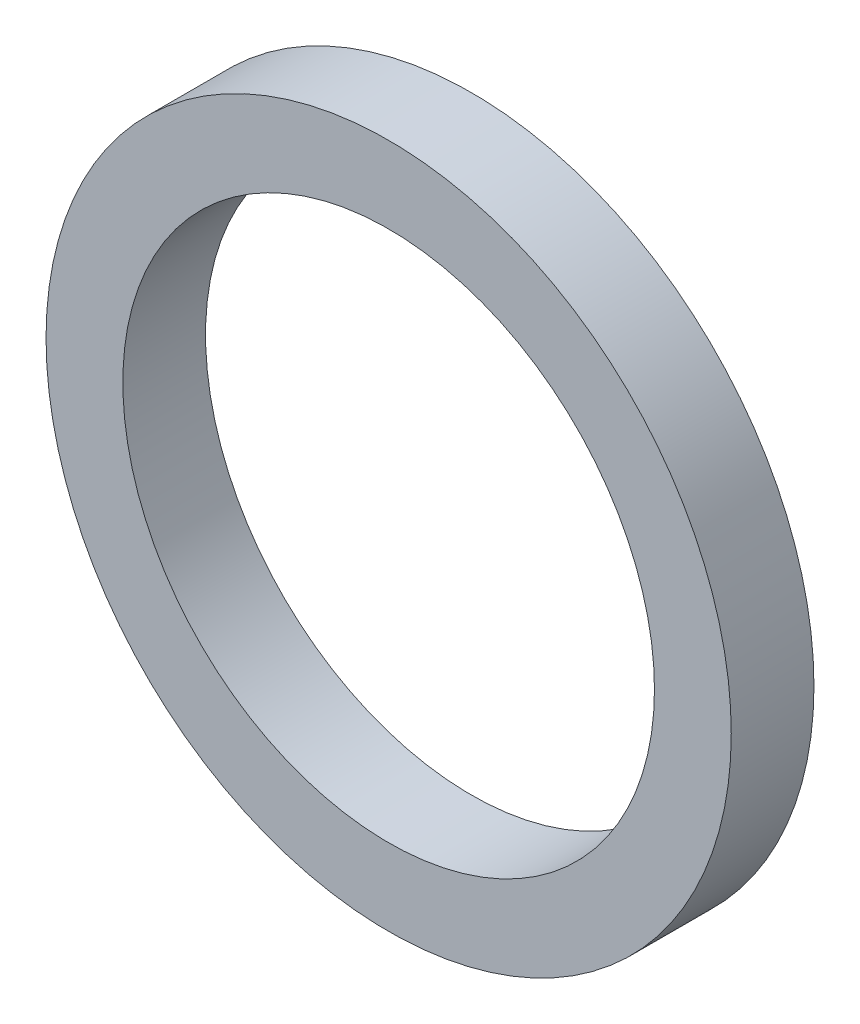
SolidWorks part; units mm, degrees
ref_plane "前视基准面" through (0, 0, 0) normal (0, 0, 1) x (1, 0, 0)
ref_plane "上视基准面" through (0, 0, 0) normal (0, 1, 0) x (1, 0, 0)
ref_plane "右视基准面" through (0, 0, 0) normal (1, 0, 0) x (0, 0, -1)
sketch "草图1" plane through (0, 0, 0) normal (0, 0, 1) x (1, 0, 0)
  circle A0 centre (0, 0) radius 22.5
  circle A1 centre (0, 0) radius 29
  dimension "D1" = 45
  dimension "D2" = 58
extrude "凸台-拉伸1" add sketch "草图1" along normal blind 7
